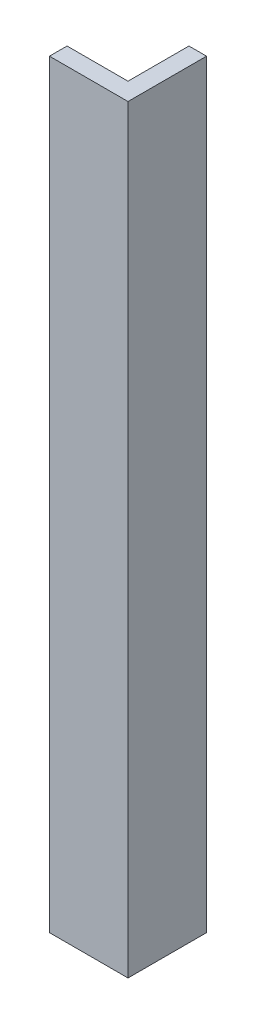
SolidWorks part; units mm, degrees
ref_plane "Front Plane" through (0, 0, 0) normal (0, 0, 1) x (1, 0, 0)
ref_plane "Top Plane" through (0, 0, 0) normal (0, 1, 0) x (1, 0, 0)
ref_plane "Right Plane" through (0, 0, 0) normal (1, 0, 0) x (0, 0, -1)
sketch "Sketch1" plane through (0, 0, 0) normal (0, 1, 0) x (1, 0, 0)
  line L1 (-3.175, 3.175) -> (-14.175, 3.175)
  line L2 (0, 14.175) -> (0, 0)
  line L3 (0, 0) -> (-14.175, 0)
  line L4 (-14.175, 3.175) -> (-14.175, 0)
  line L7 (0, 14.175) -> (-3.175, 14.175)
  line L8 (-3.175, 3.175) -> (-3.175, 14.175)
  dimension "D1" = 3.175
  dimension "D2" = 11
extrude "Boss-Extrude1" add sketch "Sketch1" along normal up to surface (137 mm away) contours L1 L4 L3 L2 L7 L8
